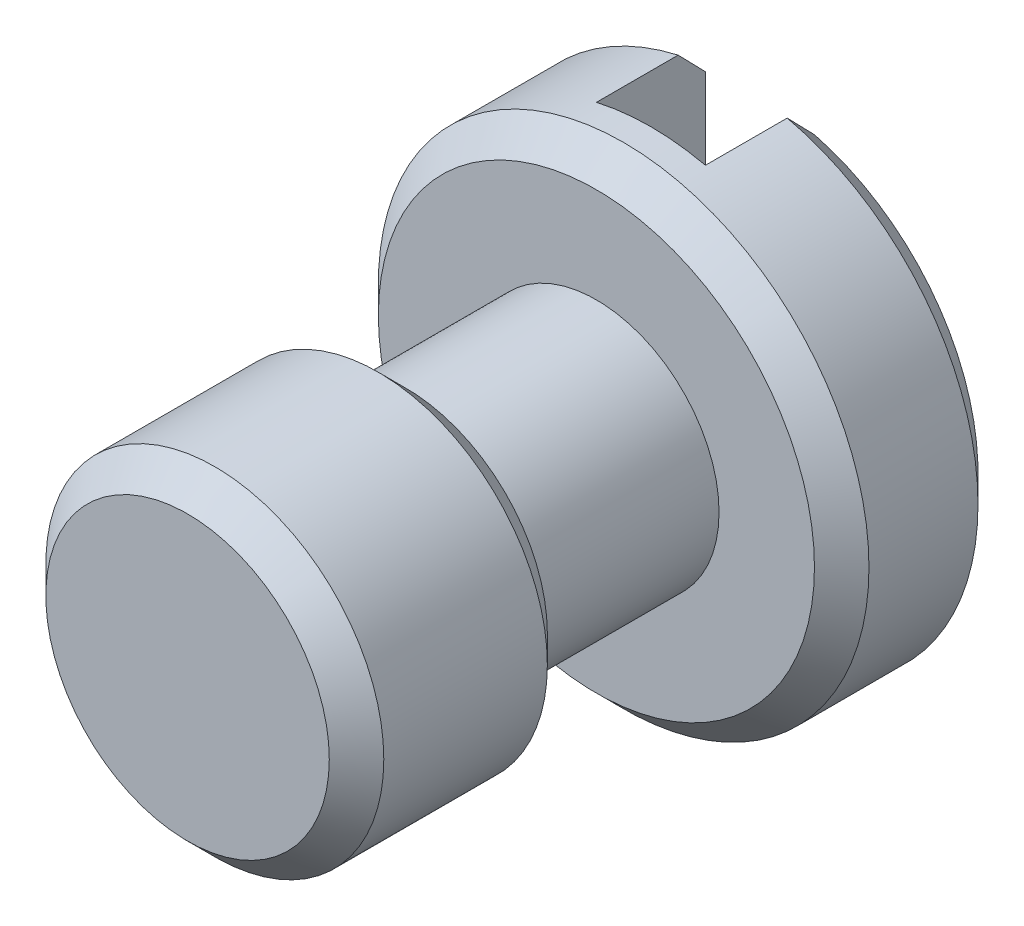
SolidWorks part; units mm, degrees
material "Сплав 2024"
ref_plane "Спереди" through (0, 0, 0) normal (0, 0, 1) x (1, 0, 0)
ref_plane "Сверху" through (0, 0, 0) normal (0, 1, 0) x (1, 0, 0)
ref_plane "Справа" through (0, 0, 0) normal (1, 0, 0) x (0, 0, -1)
sketch "Эскиз1" plane through (0, 0, 0) normal (0, 0, 1) x (1, 0, 0)
  circle A0 centre (0, 0) radius 4.5
  dimension "D1" = 9
extrude "Бобышка-Вытянуть1" add sketch "Эскиз1" along normal blind 3
sketch "Эскиз2" plane through (0, 0, 3) normal (0, 0, 1) x (1, 0, 0)
  circle A0 centre (0, 0) radius 2.25
  dimension "D1" = 4.5
extrude "Бобышка-Вытянуть2" add sketch "Эскиз2" along normal blind 3.5
sketch "Эскиз3" plane through (0, 0, 6.5) normal (0, 0, 1) x (1, 0, 0)
  circle A0 centre (0, 0) radius 3.1
  dimension "D1" = 6.2
extrude "Бобышка-Вытянуть3" add sketch "Эскиз3" along normal blind 4
chamfer "Фаска1" distance 0.5 angle 45 4 edges at (3.1, 0, 10.5) (3.1, 0, 6.5) (4.5, 0, 3) (4.5, 0, 0)
sketch "Эскиз4" plane through (0, 0, 0) normal (0, 0, -1) x (-1, 0, 0)
  line L1 (-1, 5.2603) -> (1, 5.2603)
  line L2 (-1, 5.2603) -> (-1, -5.2603)
  line L3 (-1, -5.2603) -> (1, -5.2603)
  line L4 (1, 5.2603) -> (1, -5.2603)
  line L5 (-1, 5.2603) -> (1, -5.2603) construction
  line L6 (-1, -5.2603) -> (1, 5.2603) construction
  point P0 (0, 0)
  dimension "D1" = 2
extrude "Вырез-Вытянуть1" cut sketch "Эскиз4" against normal blind 2
